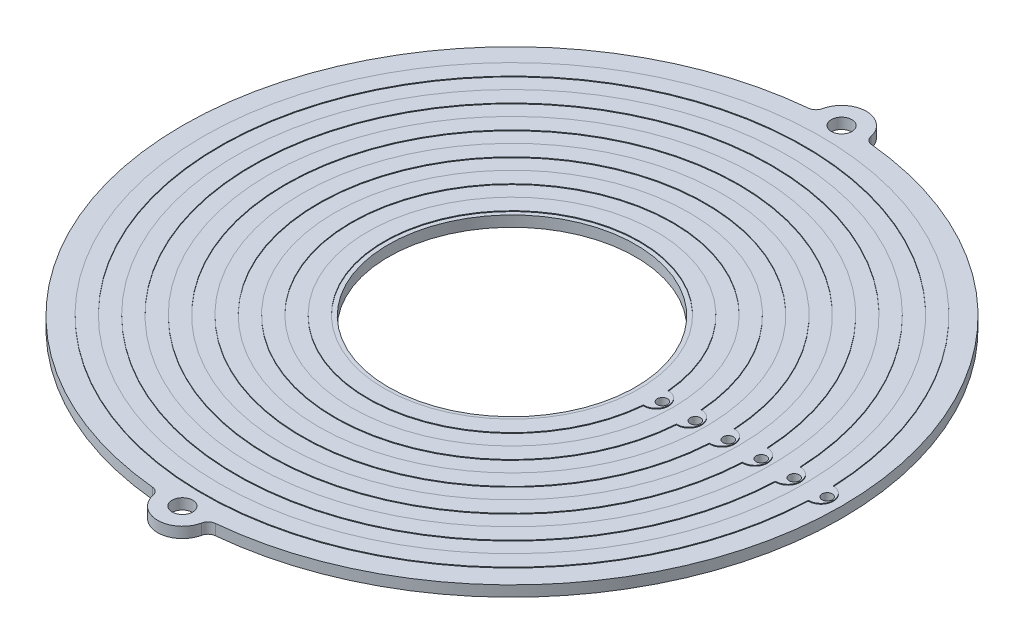
SolidWorks part; units mm, degrees
ref_plane "Front Plane" through (0, 0, 0) normal (0, 0, 1) x (1, 0, 0)
ref_plane "Top Plane" through (0, 0, 0) normal (0, 1, 0) x (1, 0, 0)
ref_plane "Right Plane" through (0, 0, 0) normal (1, 0, 0) x (0, 0, -1)
sketch "Sketch1" plane through (0, 0, 0) normal (0, 1, 0) x (1, 0, 0)
  arc A0 (-40, 0) -> (-2.9979, -39.8875) centre (0, 0) ccw
  circle A1 centre (0, 0) radius 15
  arc A2 (2.9979, 39.8875) -> (-2.9979, 39.8875) centre (0, 40) ccw
  arc A3 (-2.9979, -39.8875) -> (2.9979, -39.8875) centre (0, -40) ccw
  arc A5 (-2.9979, 39.8875) -> (-40, 0) centre (0, 0) ccw
  arc A6 (2.9979, -39.8875) -> (2.9979, 39.8875) centre (0, 0) ccw
  circle A7 centre (0, 40) radius 1.25
  circle A9 centre (0, -40) radius 1.25
  dimension "D1" = 80
  dimension "D2" = 30
  dimension "D3" = 6
  dimension "D4" = 2.5
extrude "Boss-Extrude1" add sketch "Sketch1" along normal blind 1.3
fillet "Fillet1" radius 1 4 edges at (2.9979, 0.65, -39.8875) (-2.9979, 0.65, -39.8875) (2.9979, 0.65, 39.8875) (-2.9979, 0.65, 39.8875)
sketch "Sketch2" plane through (0, 1.3, 0) normal (0, 1, 0) x (1, 0, 0)
  line L0 (37.5, 0) -> (39, 0) construction
  arc A0 (37.47, 1.4997) -> (37.47, -1.4997) centre (0, 0) ccw
  circle A1 centre (0, 0) radius 35.5
  arc A14 (37.47, -1.4997) -> (37.47, 1.4997) centre (37.5, 0) ccw
  circle A15 centre (38.25, 0) radius 0.625
  circle A16 centre (0, 0) radius 37.5 construction
  dimension "D1" = 75
  dimension "D3" = 3
  dimension "D4" = 1.25
  dimension "D2" = 2
extrude "Boss-Extrude2" add sketch "Sketch2" along normal blind 0.1
sketch "Sketch4" plane through (0, 1.3, 0) normal (0, 1, 0) x (1, 0, 0)
  line L0 (-0.735, 0) -> (0.765, 0) construction
  line L1 (33.5, 0) -> (35, 0) construction
  arc A0 (33.4664, -1.4996) -> (33.4664, 1.4996) centre (33.5, 0) ccw
  circle A1 centre (0, 0) radius 31.5
  circle A2 centre (0, 0) radius 33.5
  arc A3 (33.4664, 1.4996) -> (33.4664, -1.4996) centre (0, 0) ccw
  arc A4 (-0.7686, -1.4996) -> (-0.7686, 1.4996) centre (-0.735, 0) ccw
  circle A5 centre (0.015, 0) radius 0.625
  circle A6 centre (34.25, 0) radius 0.625
  circle A7 centre (0, 0) radius 33.5 construction
  circle A8 centre (0, 0) radius 15 construction
  dimension "D3" = 3
  dimension "D4" = 1.25
  dimension "D5" = 0.015
  dimension "D1" = 2
  dimension "D2" = 2
extrude "Boss-Extrude4" add sketch "Sketch4" along normal blind 0.1 contours A0 A3 A6 A1
sketch "Sketch5" plane through (0, 1.3, 0) normal (0, 1, 0) x (1, 0, 0)
  line L0 (29.5, 0) -> (31, 0) construction
  circle A1 centre (0, 0) radius 27.5
  circle A2 centre (0, 0) radius 29.5
  arc A3 (29.4619, 1.4995) -> (29.4619, -1.4995) centre (0, 0) ccw
  arc A4 (29.4619, -1.4995) -> (29.4619, 1.4995) centre (29.5, 0) ccw
  circle A5 centre (30.25, 0) radius 0.625
  circle A6 centre (0, 0) radius 29.5 construction
  circle A7 centre (0, 0) radius 15 construction
  dimension "D3" = 3
  dimension "D4" = 1.25
  dimension "D1" = 2
  dimension "D2" = 2
extrude "Boss-Extrude5" add sketch "Sketch5" along normal blind 0.1
sketch "Sketch6" plane through (0, 1.3, 0) normal (0, 1, 0) x (1, 0, 0)
  line L0 (25.5, 0) -> (27, 0) construction
  circle A1 centre (0, 0) radius 23.5
  circle A2 centre (0, 0) radius 25.5
  arc A3 (25.4559, 1.4994) -> (25.4559, -1.4994) centre (0, 0) ccw
  arc A4 (25.4559, -1.4994) -> (25.4559, 1.4994) centre (25.5, 0) ccw
  circle A5 centre (26.25, 0) radius 0.625
  circle A6 centre (0, 0) radius 25.5 construction
  circle A7 centre (0, 0) radius 15 construction
  dimension "D3" = 3
  dimension "D4" = 1.25
  dimension "D1" = 2
  dimension "D2" = 2
extrude "Boss-Extrude6" add sketch "Sketch6" along normal blind 0.1
sketch "Sketch7" plane through (0, 1.3, 0) normal (0, 1, 0) x (1, 0, 0)
  line L0 (21.5, 0) -> (23, 0) construction
  circle A1 centre (0, 0) radius 19.5
  circle A2 centre (0, 0) radius 21.5
  arc A3 (21.4477, 1.4991) -> (21.4477, -1.4991) centre (0, 0) ccw
  arc A4 (21.4477, -1.4991) -> (21.4477, 1.4991) centre (21.5, 0) ccw
  circle A5 centre (22.25, 0) radius 0.625
  circle A6 centre (0, 0) radius 21.5 construction
  circle A7 centre (0, 0) radius 15 construction
  dimension "D3" = 3
  dimension "D4" = 1.25
  dimension "D1" = 2
  dimension "D2" = 2
extrude "Boss-Extrude7" add sketch "Sketch7" along normal blind 0.1
sketch "Sketch8" plane through (0, 1.3, 0) normal (0, 1, 0) x (1, 0, 0)
  line L0 (17.5, 0) -> (19, 0) construction
  circle A1 centre (0, 0) radius 15.5
  circle A2 centre (0, 0) radius 17.5
  arc A3 (17.4357, 1.4986) -> (17.4357, -1.4986) centre (0, 0) ccw
  arc A4 (17.4357, -1.4986) -> (17.4357, 1.4986) centre (17.5, 0) ccw
  circle A5 centre (18.25, 0) radius 0.625
  circle A6 centre (0, 0) radius 17.5 construction
  circle A7 centre (0, 0) radius 15 construction
  dimension "D3" = 3
  dimension "D4" = 1.25
  dimension "D1" = 2
  dimension "D2" = 2
extrude "Boss-Extrude8" add sketch "Sketch8" along normal blind 0.1
sketch "Sketch12" plane through (0, 0, 0) normal (0, -1, 0) x (1, 0, 0)
  line L0 (3.7256, 38.8216) -> (3.5106, 36.5819)
  line L1 (3.5106, -36.5819) -> (3.7256, -38.8216)
  arc A1 (3.5106, -36.5819) -> (3.5106, 36.5819) centre (0, 0) ccw
  arc A2 (3.7256, -38.8216) -> (3.7256, 38.8216) centre (0, 0) ccw
  arc A3 (3.7256, -38.8216) -> (3.7256, 38.8216) centre (0, 0) ccw
  dimension "D1" = 1
  dimension "D2" = 2.25
extrude "Boss-Extrude9" add sketch "Sketch12" along normal blind 0.1
sketch "Sketch13" plane through (0, 0, 0) normal (0, -1, 0) x (1, 0, 0)
  line L0 (3.3673, 35.0888) -> (3.1285, 32.6002)
  line L1 (3.3673, -35.0888) -> (3.1285, -32.6002)
  arc A1 (3.1285, -32.6002) -> (3.1285, 32.6002) centre (0, 0) ccw
  arc A2 (3.3673, -35.0888) -> (3.3673, 35.0888) centre (0, 0) ccw
  arc A3 (3.3673, -35.0888) -> (3.3673, 35.0888) centre (0, 0) ccw
  dimension "D1" = 1.5
  dimension "D2" = 2.5
extrude "Boss-Extrude10" add sketch "Sketch13" along normal blind 0.1
sketch "Sketch14" plane through (0, 0, 0) normal (0, -1, 0) x (1, 0, 0)
  line L0 (2.9852, 31.1071) -> (2.7464, 28.6185)
  line L1 (2.9852, -31.1071) -> (2.7464, -28.6185)
  arc A1 (2.7464, -28.6185) -> (2.7464, 28.6185) centre (0, 0) ccw
  arc A2 (2.9852, -31.1071) -> (2.9852, 31.1071) centre (0, 0) ccw
  arc A3 (2.9852, -31.1071) -> (2.9852, 31.1071) centre (0, 0) ccw
  dimension "D1" = 1.5
  dimension "D2" = 2.5
extrude "Boss-Extrude11" add sketch "Sketch14" along normal blind 0.1
sketch "Sketch15" plane through (0, 0, 0) normal (0, -1, 0) x (1, 0, 0)
  line L0 (2.6031, 27.1254) -> (2.3643, 24.6368)
  line L1 (2.6031, -27.1254) -> (2.3643, -24.6368)
  arc A1 (2.3643, -24.6368) -> (2.3643, 24.6368) centre (0, 0) ccw
  arc A2 (2.6031, -27.1254) -> (2.6031, 27.1254) centre (0, 0) ccw
  arc A3 (2.6031, -27.1254) -> (2.6031, 27.1254) centre (0, 0) ccw
  dimension "D1" = 1.5
  dimension "D2" = 2.5
extrude "Boss-Extrude12" add sketch "Sketch15" along normal blind 0.1
sketch "Sketch16" plane through (0, 0, 0) normal (0, -1, 0) x (1, 0, 0)
  line L0 (1.9822, 20.6551) -> (2.221, 23.1437)
  line L1 (2.221, -23.1437) -> (1.9822, -20.6551)
  arc A1 (1.9822, -20.6551) -> (1.9822, 20.6551) centre (0, 0) ccw
  arc A2 (2.221, -23.1437) -> (2.221, 23.1437) centre (0, 0) ccw
  arc A3 (2.221, -23.1437) -> (2.221, 23.1437) centre (0, 0) ccw
  dimension "D1" = 1.5
  dimension "D2" = 2.5
extrude "Boss-Extrude13" add sketch "Sketch16" along normal blind 0.1
sketch "Sketch17" plane through (0, 0, 0) normal (0, -1, 0) x (1, 0, 0)
  line L0 (1.8389, 19.162) -> (1.6001, 16.6734)
  line L1 (1.8389, -19.162) -> (1.6001, -16.6734)
  arc A13 (1.6001, -16.6734) -> (1.6001, 16.6734) centre (0, 0) ccw
  arc A14 (1.8389, -19.162) -> (1.8389, 19.162) centre (0, 0) ccw
  arc A15 (1.8389, -19.162) -> (1.8389, 19.162) centre (0, 0) ccw
  dimension "D1" = 1.5
  dimension "D2" = 2.5
extrude "Boss-Extrude14" add sketch "Sketch17" along normal blind 0.1
sketch "Sketch10" plane through (0, 1.3, 0) normal (0, 1, 0) x (1, 0, 0)
  circle A2 centre (38.25, 0) radius 0.625
  circle A3 centre (38.25, 0) radius 0.625
  circle A5 centre (34.25, 0) radius 0.625
  circle A6 centre (34.25, 0) radius 0.625
  circle A8 centre (30.25, 0) radius 0.625
  circle A9 centre (30.25, 0) radius 0.625
  circle A11 centre (26.25, 0) radius 0.625
  circle A12 centre (26.25, 0) radius 0.625
  circle A14 centre (22.25, 0) radius 0.625
  circle A15 centre (22.25, 0) radius 0.625
  circle A17 centre (18.25, 0) radius 0.625
  circle A18 centre (18.25, 0) radius 0.625
  dimension "D1" = 0
  dimension "D2" = 0
  dimension "D3" = 0
  dimension "D4" = 0
  dimension "D5" = 0
  dimension "D6" = 0
extrude "Cut-Extrude1" cut sketch "Sketch10" against normal blind 1.5
